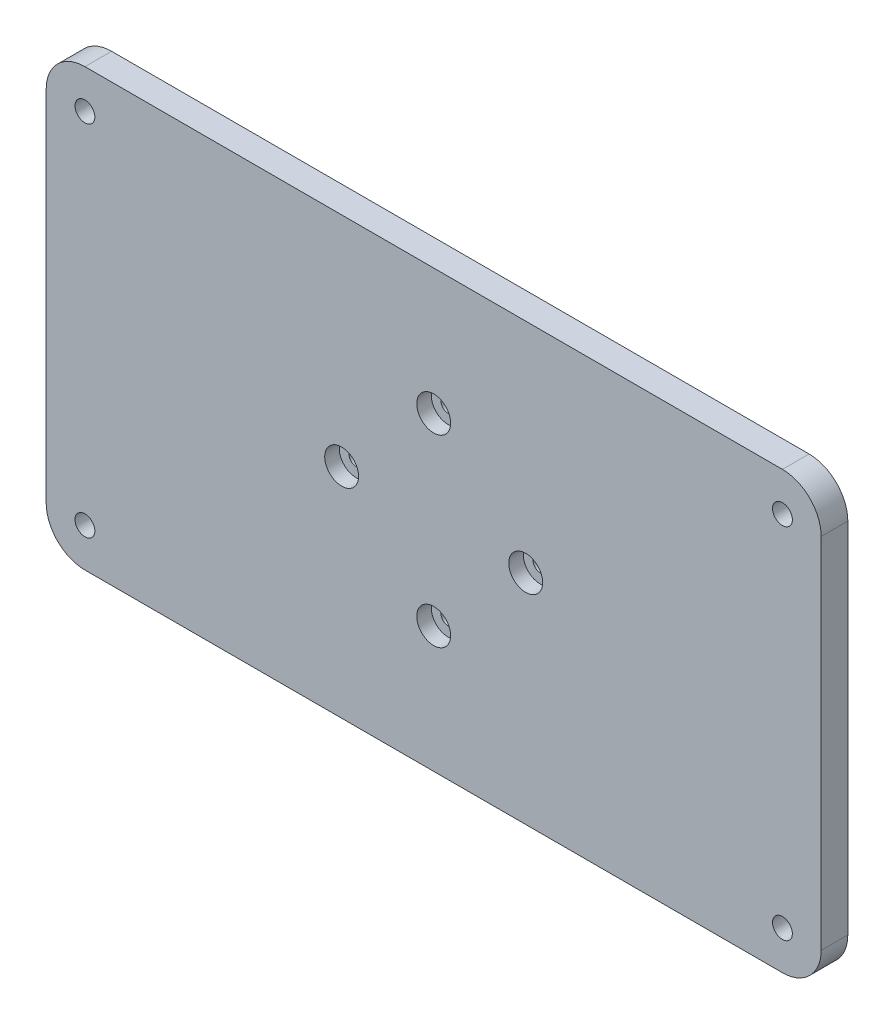
SolidWorks part; units mm, degrees
ref_plane "前视基准面" through (0, 0, 0) normal (0, 0, 1) x (1, 0, 0)
ref_plane "上视基准面" through (0, 0, 0) normal (0, 1, 0) x (1, 0, 0)
ref_plane "右视基准面" through (0, 0, 0) normal (1, 0, 0) x (0, 0, -1)
other "Configuration Table"
sketch "草图1" plane through (0, 0, 0) normal (0, 0, 1) x (1, 0, 0)
  line L0 (0, 19) -> (0, 0) construction
  circle A0 centre (0, 19) radius 1.5
  circle A1 centre (0, 0) radius 28.7
  circle A2 centre (19, 0) radius 1.5
  circle A3 centre (0, -19) radius 1.5
  circle A4 centre (-19, 0) radius 1.5
  point P14 (0, 0)
  dimension "D1" = 3
  dimension "D3" = 57.4
  dimension "D2" = 19
  dimension "D4" = 4
extrude "凸台-拉伸1" add sketch "草图1" along normal blind 3
sketch "草图2" plane through (0, 0, 3) normal (0, 0, 1) x (1, 0, 0)
  circle A0 centre (0, 0) radius 34.7
  circle A1 centre (0, 0) radius 28.7
  circle A2 centre (0, 0) radius 28.7
  dimension "D1" = 0
  dimension "D2" = 6
extrude "凸台-拉伸2" add sketch "草图2" against normal blind 48
ref_plane "基准面1" through (-24.5366, 24.5366, 0) normal (-0.7071, 0.7071, 0) x (0, 0, 1)
sketch "草图3" plane through (-24.5366, 24.5366, 0) normal (-0.7071, 0.7071, 0) x (0, 0, 1)
  line L0 (0, 28.7) -> (0, -28.7) construction
  line L1 (0, 28.7) -> (0, -28.7)
  line L2 (-12, -11.5) -> (0, -11.5)
  line L3 (-12, -11.5) -> (-12, 11.5)
  line L4 (0, -11.5) -> (0, 11.5)
  line L5 (-12, 11.5) -> (0, 11.5)
  line L6 (-12, -11.5) -> (0, 11.5) construction
  line L7 (0, -11.5) -> (-12, 11.5) construction
  point P3 (-6, 0)
  point P4 (0, 0)
  dimension "D1" = 12
  dimension "D2" = 23
extrude "切除-拉伸1" cut sketch "草图3" against normal blind 10 contours L5 L3 L2 L1
fillet "圆角1" radius 2 4 edges at (-12.74, 29.0035, 0) (-29.0035, 12.74, 0) (-29.0035, 12.74, -12) (-12.74, 29.0035, -12)
ref_plane "基准面2" through (24.5366, 24.5366, 0) normal (0.7071, 0.7071, 0) x (0.7071, -0.7071, 0)
sketch "草图4" plane through (24.5366, 24.5366, 0) normal (0.7071, 0.7071, 0) x (0.7071, -0.7071, 0)
  line L0 (28.7, 0) -> (-27.0821, 0) construction
  line L1 (28.7, 0) -> (-27.0821, 0)
  line L2 (34.7, 45) -> (-34.7, 45) construction
  line L3 (-14.191, 35) -> (15.809, 35)
  line L4 (-14.191, 35) -> (-14.191, 10)
  line L5 (-14.191, 10) -> (15.809, 10)
  line L6 (15.809, 35) -> (15.809, 10)
  line L7 (-14.191, 35) -> (15.809, 10) construction
  line L8 (-14.191, 10) -> (15.809, 35) construction
  point P2 (0.809, 22.5)
  point P8 (0.809, 0)
  dimension "D1" = 10
  dimension "D2" = 10
  dimension "D3" = 30
extrude "切除-拉伸2" cut sketch "草图4" against normal through all contours L6 L3 L4 L5
fillet "圆角2" radius 2 8 edges at (-8.2113, -30.5686, -35) (30.5686, 8.2113, -35) (-30.0498, -9.9806, -35) (9.9806, 30.0498, -35) (-30.0498, -9.9806, -10) (9.9806, 30.0498, -10) (-8.2113, -30.5686, -10) (30.5686, 8.2113, -10)
sketch "草图5" plane through (0, 0, 3) normal (0, 0, 1) x (1, 0, 0)
  line L1 (-80, 45) -> (80, 45)
  line L2 (-80, 45) -> (-80, -45)
  line L3 (-80, -45) -> (80, -45)
  line L4 (80, 45) -> (80, -45)
  line L5 (-80, 45) -> (80, -45) construction
  line L6 (-80, -45) -> (80, 45) construction
  circle A1 centre (0, 0) radius 34.7
  circle A2 centre (0, 0) radius 34.7
  circle A3 centre (0, 19) radius 1.5
  circle A4 centre (0, 19) radius 1.5
  circle A5 centre (19, 0) radius 1.5
  circle A6 centre (19, 0) radius 1.5
  circle A7 centre (0, -19) radius 1.5
  circle A8 centre (0, -19) radius 1.5
  circle A9 centre (-19, 0) radius 1.5
  circle A10 centre (-19, 0) radius 1.5
  circle M8 centre (0, -19) radius 1.5
  circle M9 centre (0, 19) radius 1.5
  circle M10 centre (19, 0) radius 1.5
  circle M11 centre (-19, 0) radius 1.5
  circle M12 centre (0, 0) radius 34.7
  dimension "D6" = 90
  dimension "D7" = 160
  dimension "D1" = 0
  dimension "D2" = 0
  dimension "D3" = 0
  dimension "D4" = 0
  dimension "D5" = 0
extrude "凸台-拉伸3" add sketch "草图5" along normal blind 5.5 contours L4 L1 L2 L3 M12 | M12 M9 M11 M10 M8
sketch "草图7" plane through (0, 0, 3) normal (0, 0, -1) x (-1, 0, 0)
  line L8 (-72, 37) -> (-72, -37)
  line L9 (-72, -37) -> (72, -37)
  line L10 (72, -37) -> (72, 37)
  line L11 (72, 37) -> (-72, 37)
  line L12 (-72, 37) -> (-72, -37) construction
  line L13 (-72, -37) -> (72, -37) construction
  line L14 (72, -37) -> (72, 37) construction
  line L15 (72, 37) -> (-72, 37) construction
  circle A0 centre (-72, 37) radius 2.05
  circle A1 centre (72, 37) radius 2.05
  circle A2 centre (72, -37) radius 2.05
  circle A3 centre (-72, -37) radius 2.05
  dimension "D2" = 4.1
  dimension "D1" = 8
extrude "切除-拉伸3" cut sketch "草图7" against normal through all
fillet "圆角4" radius 8 4 edges at (-80, -45, 5.75) (-80, 45, 5.75) (80, 45, 5.75) (80, -45, 5.75)
sketch "草图8" plane through (0, 0, 8.5) normal (0, 0, 1) x (1, 0, 0)
  circle A0 centre (-19, 0) radius 1.5 construction
  circle A1 centre (-19, 0) radius 1.5
  circle A2 centre (-19, 0) radius 3.5
  circle A3 centre (0, 19) radius 3.5
  circle A4 centre (19, 0) radius 3.5
  circle A5 centre (0, -19) radius 3.5
  point P13 (0, 0)
  dimension "D1" = 7
  dimension "D2" = 4
extrude "切除-拉伸4" cut sketch "草图8" against normal blind 3
sketch "草图9" plane through (0, 0, -45) normal (0, 0, -1) x (-1, 0, 0)
  circle A1 centre (0, 0) radius 34.7
  circle A2 centre (0, 0) radius 34.7
  dimension "D1" = 0
extrude "切除-拉伸5" cut sketch "草图9" against normal up to surface (48 mm away) up to face at (69.95, -37, 3)
